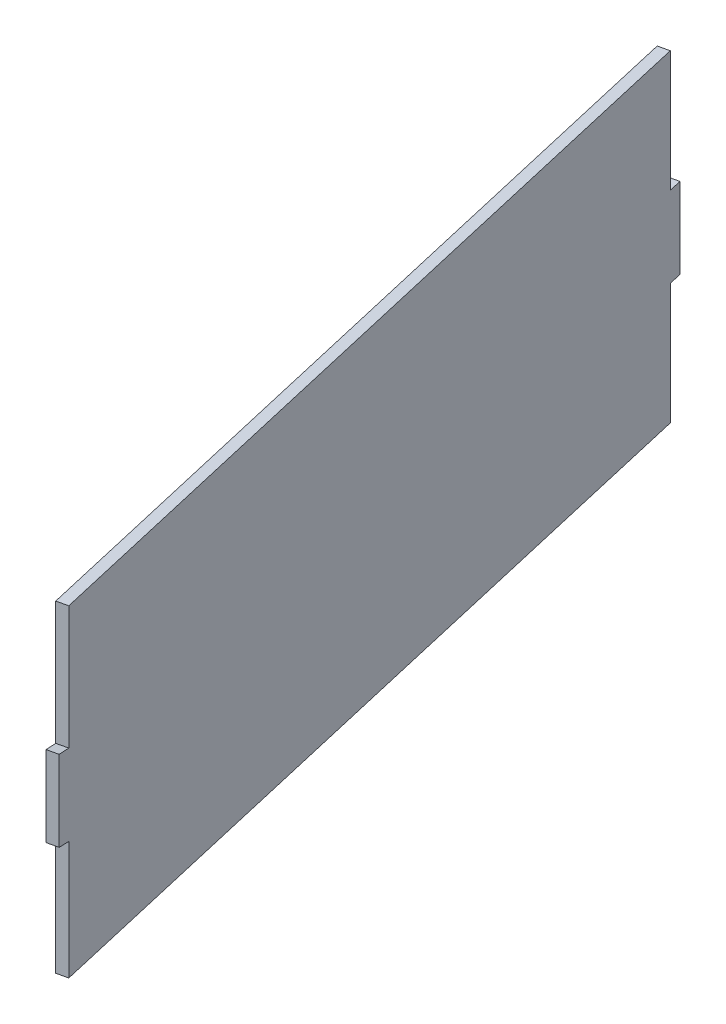
SolidWorks part; units mm, degrees
ref_plane "Front Plane" through (0, 0, 0) normal (0, 0, 1) x (1, 0, 0)
ref_plane "Top Plane" through (0, 0, 0) normal (0, 1, 0) x (1, 0, 0)
ref_plane "Right Plane" through (0, 0, 0) normal (1, 0, 0) x (0, 0, -1)
sketch "Sketch1" plane through (847.601, 0, -195.2086) normal (0.9745, 0, -0.2244) x (-0.2244, 0, -0.9745)
  line L3 (2652.8255, -41.5816) -> (1906.4982, -41.5816)
  line L4 (1906.4982, -41.5816) -> (1906.4982, -156.2542)
  line L5 (1944.5892, -41.5816) -> (1906.4982, -41.5816) construction
  line L6 (1906.4982, -41.5816) -> (1906.4982, -341.5816) construction
  line L7 (2664.8255, -154.0816) -> (2664.8255, -229.0816)
  line L8 (2664.8255, -229.0816) -> (2652.8255, -229.0816)
  line L9 (2652.8255, -229.0816) -> (2652.8255, -341.5816)
  line L10 (2652.8255, -341.5816) -> (1906.4982, -341.5816)
  line L11 (2762.7613, -154.0816) -> (1906.4982, -154.0816) construction
  line L12 (2279.6619, -341.5816) -> (2279.6619, -41.5816) construction
  line L13 (1894.4982, -229.0816) -> (1906.4982, -231.5124)
  line L14 (1894.4982, -154.0816) -> (1894.4982, -229.0816)
  line L15 (1894.4982, -154.0816) -> (1906.4982, -156.2542)
  line L16 (1906.4982, -231.5124) -> (1906.4982, -341.5816)
  line L17 (2652.8255, -41.5816) -> (2652.8255, -154.0816)
  line L18 (2762.7613, -154.0816) -> (2762.7613, -229.0816) construction
  line L20 (2652.8255, -154.0816) -> (2664.8255, -154.0816)
  line L21 (2652.8255, -154.0816) -> (2652.8255, -229.0816) construction
  dimension "D1" = 12
  dimension "D2" = 75
extrude "Boss-Extrude1" add sketch "Sketch1" against normal blind 10.16
